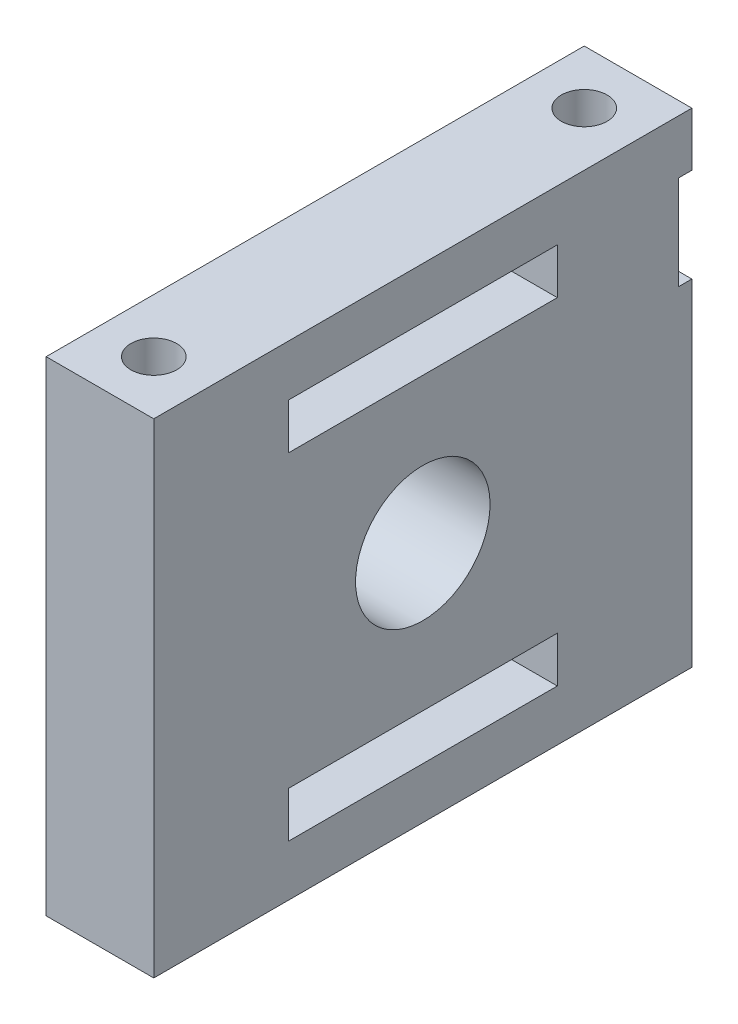
SolidWorks part; units mm, degrees
ref_plane "Front" through (0, 0, 0) normal (0, 0, 1) x (1, 0, 0)
ref_plane "Top" through (0, 0, 0) normal (0, 1, 0) x (1, 0, 0)
ref_plane "Right" through (0, 0, 0) normal (1, 0, 0) x (0, 0, -1)
sketch "Sketch1" plane through (0, 0, 0) normal (1, 0, 0) x (0, 0, -1)
  line L1 (0, 0) -> (40, 0)
  line L2 (0, 0) -> (0, -36)
  line L3 (0, -36) -> (40, -36)
  line L4 (40, 0) -> (40, -36)
  dimension "D1" = 40
  dimension "D2" = 36
extrude "Boss-Extrude1" add sketch "Sketch1" along normal blind 8
sketch "Sketch2" plane through (8, 0, 0) normal (1, 0, 0) x (0, 0, -1)
  line L0 (40, 0) -> (0, 0) construction
  line L1 (0, 0) -> (0, -36) construction
  circle A0 centre (20, -18) radius 5
  dimension "D1" = 10
  dimension "D2" = 18
  dimension "D3" = 20
extrude "Cut-Extrude1" cut sketch "Sketch2" against normal through all
sketch "Sketch3" plane through (8, 0, 0) normal (1, 0, 0) x (0, 0, -1)
  line L0 (40, -36) -> (40, 0) construction
  line L1 (10, -3.8) -> (30, -3.8)
  line L2 (10, -3.8) -> (10, -7.2)
  line L3 (10, -7.2) -> (30, -7.2)
  line L4 (30, -3.8) -> (30, -7.2)
  line L5 (40, 0) -> (0, 0) construction
  line L6 (10, -32.2) -> (30, -32.2)
  line L7 (10, -28.8) -> (30, -28.8)
  line L8 (30, -28.8) -> (30, -32.2)
  line L9 (10, -28.8) -> (10, -32.2)
  dimension "D1" = 3.4
  dimension "D2" = 20
  dimension "D3" = 10
  dimension "D4" = 3.8
  dimension "D5" = 2
extrude "Cut-Extrude2" cut sketch "Sketch3" against normal through all
sketch "Sketch6" plane through (0, 0, 0) normal (0, 1, 0) x (1, 0, 0)
  line L0 (8, 40) -> (8, 0) construction
  line L1 (8, 0) -> (0, 0) construction
  circle A0 centre (4, 4) radius 1.7
  circle A1 centre (4, 36) radius 1.7
  dimension "D1" = 3.4
  dimension "D2" = 4
  dimension "D3" = 4
  dimension "D4" = 2
extrude "Cut-Extrude3" cut sketch "Sketch6" against normal through all
sketch "Sketch7" plane through (8, 0, 0) normal (1, 0, 0) x (0, 0, -1)
  line L0 (40, -36) -> (40, 0) construction
  line L1 (40, -11) -> (39, -11)
  line L2 (40, -11) -> (40, -4)
  line L3 (40, -4) -> (39, -4)
  line L4 (39, -11) -> (39, -4)
  line L5 (40, 0) -> (0, 0) construction
  line L6 (0, -36) -> (40, -36) construction
  dimension "D1" = 1
  dimension "D2" = 4
  dimension "D3" = 25
extrude "Cut-Extrude4" cut sketch "Sketch7" against normal through all
equation "\"offset\"= 0.4"
equation "\"D1@Sketch3\"=\"offset\"+3"
equation "\"D1@Sketch6\"=\"offset\"+3"
